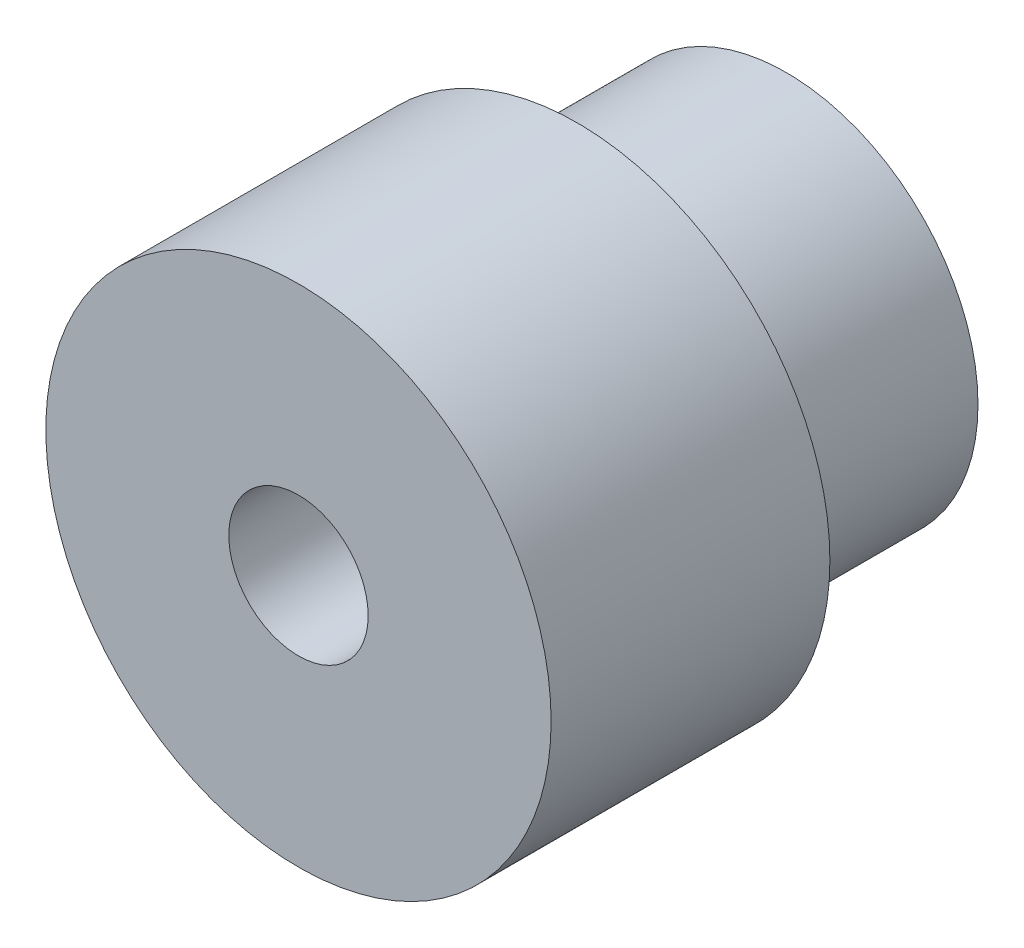
SolidWorks part; units mm, degrees
ref_plane "Front Plane" through (0, 0, 0) normal (0, 0, 1) x (1, 0, 0)
ref_plane "Top Plane" through (0, 0, 0) normal (0, 1, 0) x (1, 0, 0)
ref_plane "Right Plane" through (0, 0, 0) normal (1, 0, 0) x (0, 0, -1)
sketch "Sketch1" plane through (0, 0, 0) normal (0, 0, 1) x (1, 0, 0)
  circle A0 centre (0, 0) radius 14.5
extrude "Boss-Extrude1" add sketch "Sketch1" along normal blind 16
sketch "Sketch2" plane through (0, 0, 0) normal (0, 0, 1) x (1, 0, 0)
  circle A0 centre (0, 0) radius 11
extrude "Boss-Extrude2" add sketch "Sketch2" against normal blind 12
sketch "Sketch3" plane through (0, 0, 0) normal (0, 0, 1) x (1, 0, 0)
  circle A0 centre (0, 0) radius 4
extrude "Cut-Extrude1" cut sketch "Sketch3" against normal through all both and the other way through all
